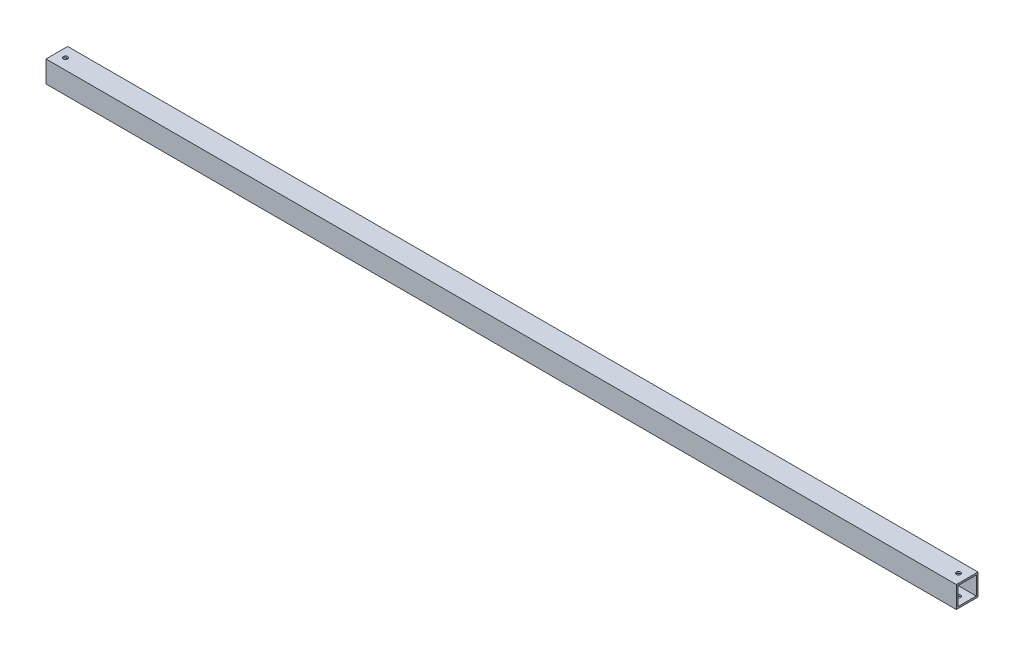
SolidWorks part; units mm, degrees
ref_plane "正面" through (0, 0, 0) normal (0, 0, 1) x (1, 0, 0)
ref_plane "平面" through (0, 0, 0) normal (0, 1, 0) x (1, 0, 0)
ref_plane "右側面" through (0, 0, 0) normal (1, 0, 0) x (0, 0, -1)
sketch "ｽｹｯﾁ1" plane through (0, 0, 0) normal (0, 0, 1) x (1, 0, 0)
  line L1 (0, 0) -> (630, 0)
  line L2 (0, 0) -> (0, 15)
  line L3 (0, 15) -> (630, 15)
  line L4 (630, 0) -> (630, 15)
  dimension "D1" = 15
  dimension "D2" = 630
extrude "ﾎﾞｽ - 押し出し1" add sketch "ｽｹｯﾁ1" along normal blind 15
sketch "ｽｹｯﾁ2" plane through (0, 15, 0) normal (0, 1, 0) x (1, 0, 0)
  line L0 (630, -7.5) -> (0, -7.5) construction
  line L1 (630, -15) -> (630, 0) construction
  line L2 (0, -15) -> (0, 0) construction
  circle A0 centre (6, -7.5) radius 1.5
  circle A1 centre (624, -7.5) radius 1.5
  dimension "D1" = 3
  dimension "D3" = 6
  dimension "D2" = 6
extrude "ｶｯﾄ - 押し出し1" cut sketch "ｽｹｯﾁ2" against normal through all
sketch "ｽｹｯﾁ3" plane through (0, 0, 0) normal (-1, 0, 0) x (0, 0, 1)
  line L8 (1.2, 13.8) -> (1.2, 1.2)
  line L9 (1.2, 1.2) -> (13.8, 1.2)
  line L10 (13.8, 1.2) -> (13.8, 13.8)
  line L11 (13.8, 13.8) -> (1.2, 13.8)
  line L12 (1.2, 13.8) -> (1.2, 1.2)
  line L13 (1.2, 1.2) -> (13.8, 1.2)
  line L14 (13.8, 1.2) -> (13.8, 13.8)
  line L15 (13.8, 13.8) -> (1.2, 13.8)
  dimension "D1" = 1.2
extrude "ｶｯﾄ - 押し出し2" cut sketch "ｽｹｯﾁ3" against normal through all
